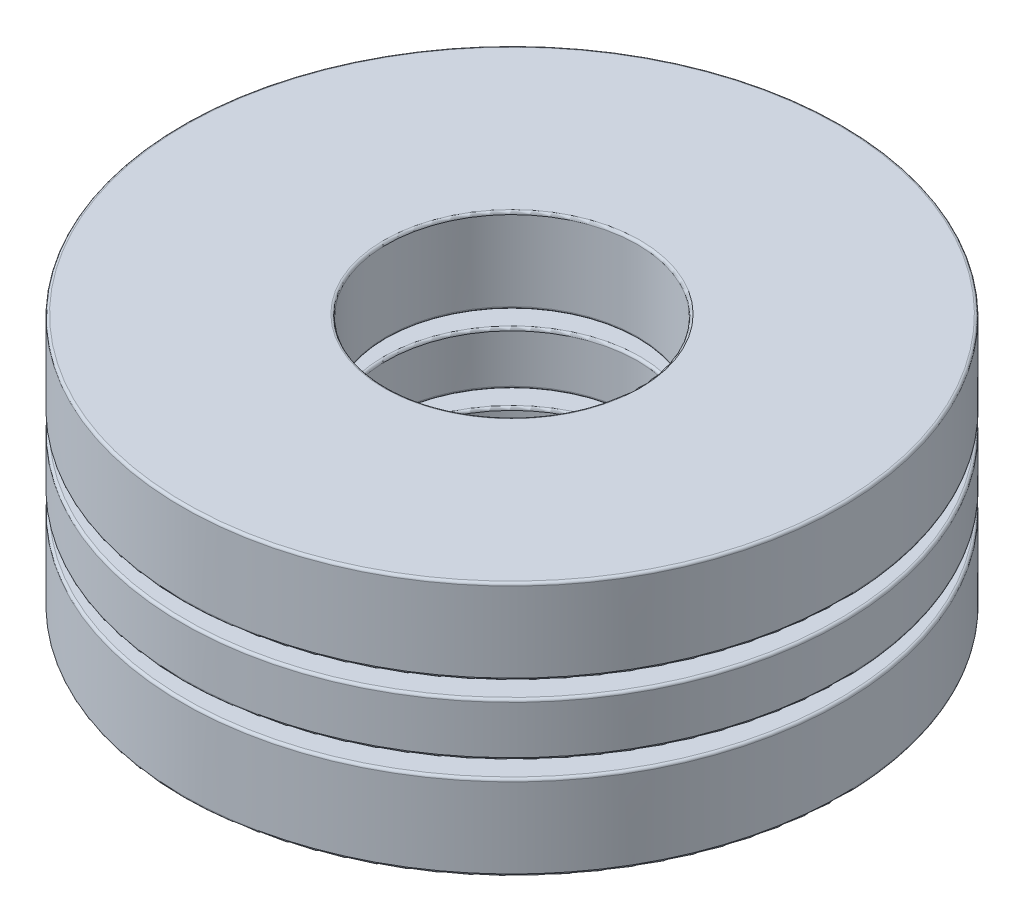
SolidWorks part; units mm, degrees
ref_plane "Front Plane" through (0, 0, 0) normal (0, 0, 1) x (1, 0, 0)
ref_plane "Top Plane" through (0, 0, 0) normal (0, 1, 0) x (1, 0, 0)
ref_plane "Right Plane" through (0, 0, 0) normal (1, 0, 0) x (0, 0, -1)
sketch "Sketch1" plane through (0, 0, 0) normal (1, 0, 0) x (0, 0, -1)
  line L0 (-6.35, 0) -> (6.35, 0) construction
  line L1 (0, -2.4511) -> (0, 2.4511) construction
  line L2 (-6.35, 0.5106) -> (-2.4193, 0.5106)
  line L3 (-6.35, 0.5106) -> (-6.35, -0.5106)
  line L4 (-6.35, -0.5106) -> (-2.4193, -0.5106)
  line L5 (-2.4193, 0.5106) -> (-2.4193, -0.5106)
  line L6 (-4.3847, 0.817) -> (-4.3847, -0.817) construction
  circle A0 centre (-4.3847, 0) radius 0.817 construction
  point P13 (-4.3847, 0.5106)
  dimension "OD" = 12.7
  dimension "Shaft Dia" = 4.8387
  dimension "Th" = 4.9022
  dimension "D1" = 1.6341
  dimension "D2" = 1.0213
revolve "Revolve1" add sketch "Sketch1" angle 360 about L1
sketch "Sketch3" plane through (0, 0, 0) normal (1, 0, 0) x (0, 0, -1)
  line L0 (-4.3847, 0.817) -> (-4.3847, -0.817)
  arc A0 (-4.3847, 0.817) -> (-4.3847, -0.817) centre (-4.3847, 0) ccw
  circle A1 centre (-4.3847, 0) radius 0.817 construction
revolve "Cut-Revolve1" cut sketch "Sketch3" angle 360 about L0
sketch "Sketch2" plane through (0, 0, 0) normal (1, 0, 0) x (0, 0, -1)
  line L0 (-4.3847, 0.817) -> (-4.3847, -0.817)
  arc A0 (-4.3847, 0.817) -> (-4.3847, -0.817) centre (-4.3847, 0) ccw
  circle A2 centre (-4.3847, 0) radius 0.817 construction
revolve "Revolve2" add sketch "Sketch2" angle 360 about L0
ref_axis "Axis1" through (0, 2.4511, 0) along (0, -1, 0)
pattern_circular "CirPattern1" count 3 every 120 about axis through (0, 2.4511, 0) along (0, -1, 0) of bodies 187
pattern_circular "CirPattern2" count 3 every 120 about axis through (0, 0, 0) along (0, 1, 0) of "Cut-Revolve1"
sketch "Sketch4" plane through (0, 0, 0) normal (1, 0, 0) x (0, 0, -1)
  line L0 (-6.35, 0.5106) -> (-6.35, -0.5106) construction
  line L1 (-6.35, 0.817) -> (-2.4193, 0.817)
  line L2 (-6.35, 0.817) -> (-6.35, 2.4511)
  line L3 (-6.35, 2.4511) -> (-2.4194, 2.4511)
  line L4 (-2.4193, 0.817) -> (-2.4194, 2.4511)
  line L5 (-6.35, -2.4511) -> (-2.4193, -2.4511)
  line L6 (-6.35, -2.4511) -> (-6.35, -0.817)
  line L7 (-6.35, -0.817) -> (-2.4193, -0.817)
  line L8 (-2.4193, -2.4511) -> (-2.4193, -0.817)
  line L9 (-4.3847, 0.817) -> (-4.3847, -0.817) construction
  line L10 (-2.4193, 0.5106) -> (-2.4193, -0.5106) construction
  line L11 (0, 0) -> (-6.35, 0) construction
  line L12 (-6.35, 0) -> (6.35, 0) construction
  dimension "Ht" = 4.9022
revolve "Revolve3" add sketch "Sketch4" angle 360 about L1
fillet "Fillet1" radius 0.049 4 edges at (0, 0.817, -2.4193) (0, 2.4511, -2.4194) (0, 0.817, -6.35) (0, 2.4511, -6.35)
fillet "Fillet2" radius 0.049 4 edges at (0, -0.5106, -2.4193) (0, 0.5106, -2.4193) (0, -0.5106, -6.35) (0, 0.5106, -6.35)
fillet "Fillet3" radius 0.049 4 edges at (0, -2.4511, -2.4193) (0, -0.817, -2.4193) (0, -2.4511, -6.35) (0, -0.817, -6.35)
equation "\"D1@Sketch1\" = \"Th@Sketch1\"/3"
equation "\"D2@Sketch1\" = \"D1@Sketch1\"*.625"
equation "\"Balls@CirPattern1\" = \"OD@Sketch1\"*5"
equation "\"Angle@CirPattern1\" = 360/\"Balls@CirPattern1\""
equation "\"D1@CirPattern2\" = \"Balls@CirPattern1\""
equation "\"D2@CirPattern2\" = \"Angle@CirPattern1\""
equation "\"D1@Fillet1\" = \"Th@Sketch1\"*.01"
equation "\"D1@Fillet2\" = \"D1@Fillet1\""
equation "\"D1@Fillet3\" = \"D1@Fillet1\""
